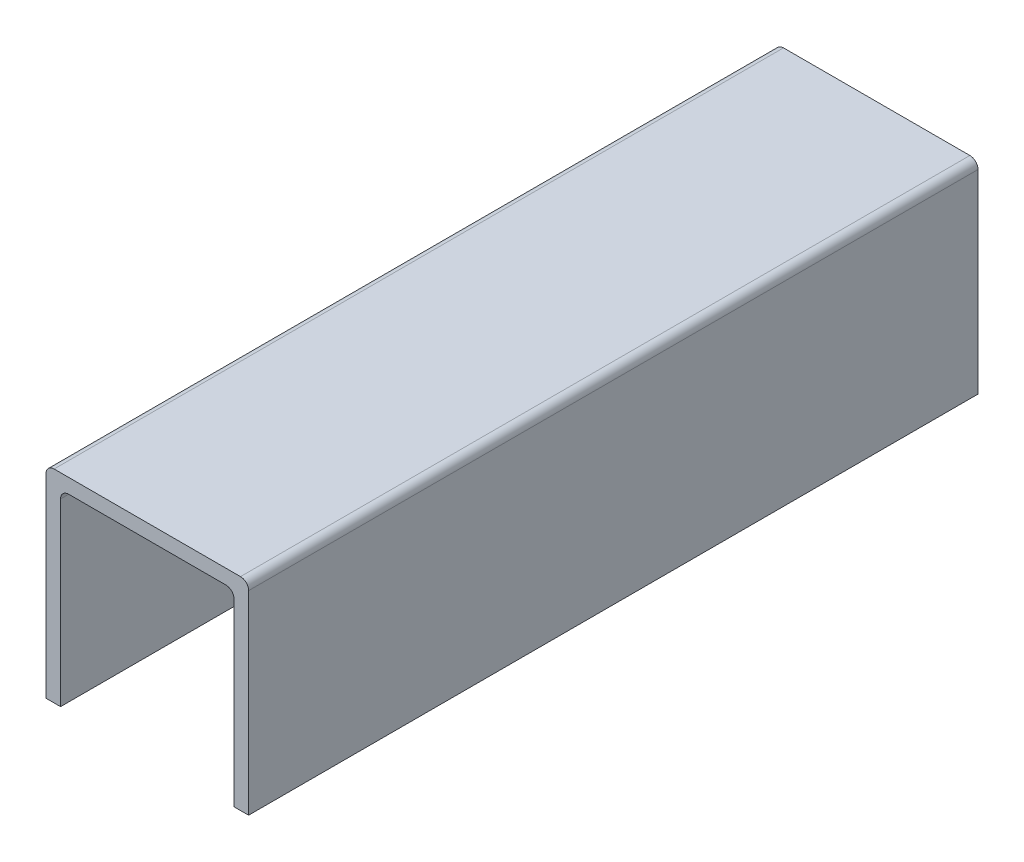
SolidWorks part; units mm, degrees
material "6061 Alloy"
ref_plane "Front Plane" through (0, 0, 0) normal (0, 0, 1) x (1, 0, 0)
ref_plane "Top Plane" through (0, 0, 0) normal (0, 1, 0) x (1, 0, 0)
ref_plane "Right Plane" through (0, 0, 0) normal (1, 0, 0) x (0, 0, -1)
sketch "Sketch1" plane through (0, 0, 0) normal (0, 0, 1) x (1, 0, 0)
  line L0 (0, 0) -> (0, 50)
  line L1 (0, 50) -> (50, 50)
  line L2 (50, 50) -> (50, 0)
  line L3 (50, 0) -> (46.405, 0)
  line L4 (46.405, 0) -> (46.405, 46.405)
  line L5 (46.405, 46.405) -> (3.595, 46.405)
  line L6 (3.595, 46.405) -> (3.595, 0)
  line L7 (3.595, 0) -> (0, 0)
  line L8 (3.595, 46.405) -> (3.595, 50) construction
  dimension "D1" = 50
  dimension "D2" = 3.595
extrude "Boss-Extrude1" add sketch "Sketch1" along normal blind 180
fillet "Fillet1" radius 2 4 edges at (3.595, 46.405, 90) (46.405, 46.405, 90) (0, 50, 90) (50, 50, 90)
